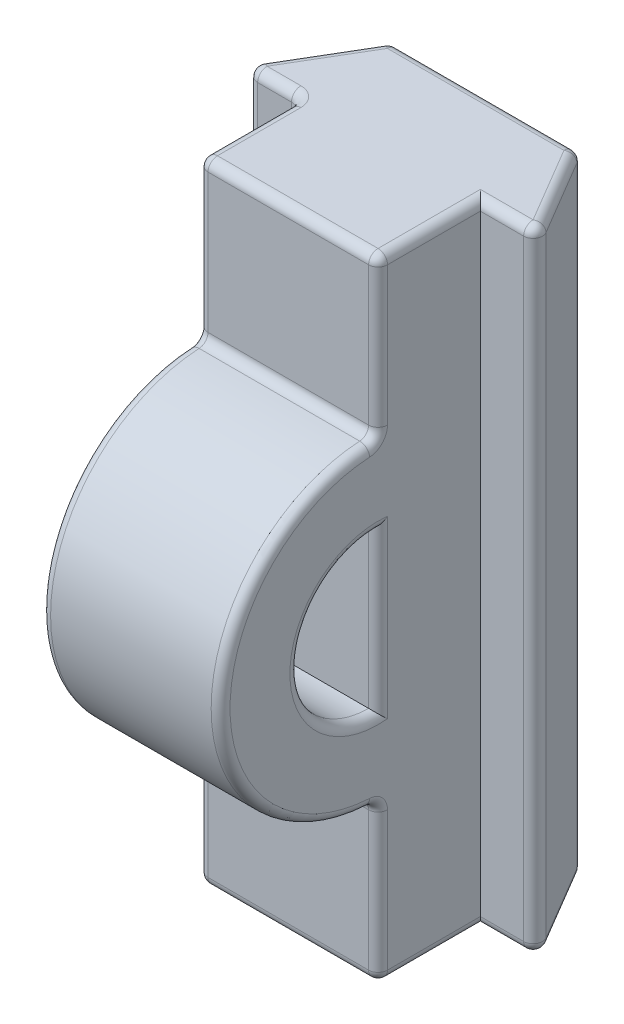
SolidWorks part; units mm, degrees
ref_plane "Front Plane" through (0, 0, 0) normal (0, 0, 1) x (1, 0, 0)
ref_plane "Top Plane" through (0, 0, 0) normal (0, 1, 0) x (1, 0, 0)
ref_plane "Right Plane" through (0, 0, 0) normal (1, 0, 0) x (0, 0, -1)
sketch "Sketch1" plane through (0, 0, 0) normal (0, 1, 0) x (1, 0, 0)
  line L0 (-2.85, 0) -> (2.85, 0)
  line L1 (-2.85, 0) -> (-2.85, 3.25)
  line L2 (-2.85, 3.25) -> (-4.75, 3.25)
  line L3 (-4.75, 3.25) -> (-2.975, 6.25)
  line L4 (-2.975, 6.25) -> (2.975, 6.25)
  line L5 (2.975, 6.25) -> (4.75, 3.25)
  line L6 (4.75, 3.25) -> (2.85, 3.25)
  line L7 (2.85, 3.25) -> (2.85, 0)
  point P4 (0, 0)
  dimension "D1" = 5.7
  dimension "D2" = 3.25
  dimension "D3" = 5.95
  dimension "D4" = 1.9
  dimension "D5" = 1.9
  dimension "D6" = 3.25
  dimension "D7" = 6.25
extrude "Boss-Extrude1" add sketch "Sketch1" along normal blind 20
sketch "Sketch3" plane through (0, 0, 0) normal (1, 0, 0) x (0, 0, -1)
  line L0 (0, 10) -> (0, 15)
  line L1 (0, 20) -> (0, 0) construction
  line L2 (0, 10) -> (0, 5)
  line L3 (0, 10) -> (0, 12.5)
  line L4 (0, 10) -> (0, 7.5)
  arc A0 (0, 15) -> (0, 5) centre (0, 10) ccw
  arc A1 (0, 12.5) -> (0, 7.5) centre (0, 10) ccw
  dimension "D1" = 5
  dimension "D2" = 5
extrude "Boss-Extrude2" add sketch "Sketch3" along normal mid plane 5.7 contours A1 L0 A0 L2
fillet "Fillet1" radius 0.3 33 edges at (2.975, 10, -6.25) (2.85, 17.5, 0) (-2.85, 17.5, 0) (2.85, 2.5, 0) (-2.85, 2.5, 0) (-2.975, 10, -6.25) (0, 20, 0) (-2.85, 20, -1.625) (-3.8, 20, -3.25) (-3.8625, 20, -4.75) (0, 20, -6.25) (3.8625, 20, -4.75) (3.8, 20, -3.25) (2.85, 20, -1.625) (3.8, 0, -3.25) (3.8625, 0, -4.75) (0, 0, -6.25) (-3.8625, 0, -4.75) (-3.8, 0, -3.25) (-2.85, 0, -1.625) (0, 0, 0) (2.85, 0, -1.625) (0, 5, 0) (0, 15, 0) (-2.85, 10, 5) (2.85, 10, 5) (-2.85, 10, 2.5) (2.85, 10, 2.5) (-2.85, 10, 0) (2.85, 10, 0) (-4.75, 10, -3.25) (-2.85, 10, -3.25) (4.75, 10, -3.25)
